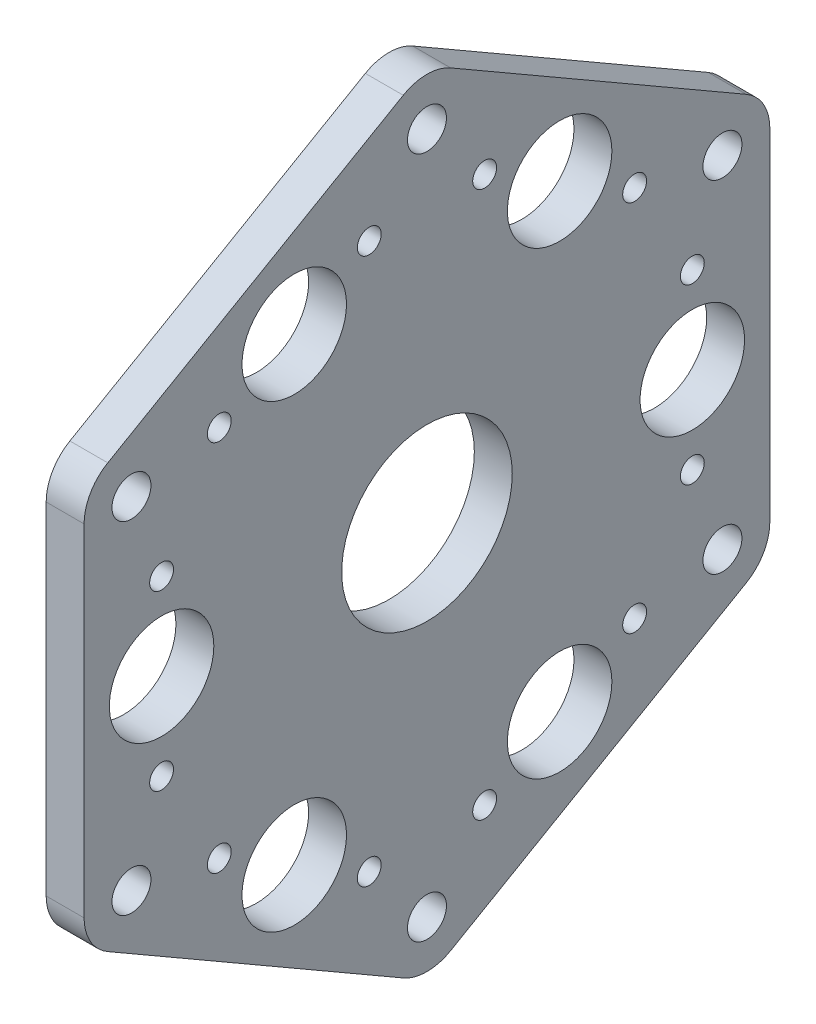
SolidWorks part; units mm, degrees
material "6061-T6 (SS)"
ref_plane "Front Plane" through (0, 0, 0) normal (0, 0, 1) x (1, 0, 0)
ref_plane "Top Plane" through (0, 0, 0) normal (0, 1, 0) x (1, 0, 0)
ref_plane "Right Plane" through (0, 0, 0) normal (1, 0, 0) x (0, 0, -1)
sketch "Sketch1" plane through (0, 0, 0) normal (1, 0, 0) x (0, 0, -1)
  line L0 (-57.4309, 28.575) -> (-57.4309, -28.575)
  line L1 (-53.4621, 35.4491) -> (-3.9687, 64.0241)
  line L2 (3.9688, 64.0241) -> (53.4621, 35.4491)
  line L3 (57.4309, 28.575) -> (57.4309, -28.575)
  line L4 (53.4621, -35.4491) -> (3.9687, -64.0241)
  line L5 (-53.4621, -35.4491) -> (-3.9688, -64.0241)
  circle A1 centre (0, -57.15) radius 3.2639 construction
  circle A3 centre (49.4934, -28.575) radius 3.2639 construction
  circle A5 centre (49.4934, 28.575) radius 3.2639 construction
  circle A8 centre (0, 57.15) radius 3.2639 construction
  circle A9 centre (-49.4934, 28.575) radius 3.2639 construction
  circle A10 centre (-49.4934, -28.575) radius 3.2639 construction
  circle A13 centre (0, -57.15) radius 3.2639
  circle A15 centre (49.4934, -28.575) radius 3.2639
  circle A17 centre (49.4934, 28.575) radius 3.2639
  circle A20 centre (0, 57.15) radius 3.2639
  circle A21 centre (-49.4934, 28.575) radius 3.2639
  circle A22 centre (-49.4934, -28.575) radius 3.2639
  circle A25 centre (-49.4934, -28.575) radius 7.9375
  circle A27 centre (-49.4934, 28.575) radius 7.9375
  circle A28 centre (0, 57.15) radius 7.9375
  circle A29 centre (49.4934, 28.575) radius 7.9375
  circle A30 centre (49.4934, -28.575) radius 7.9375
  circle A31 centre (0, -57.15) radius 7.9375
  dimension "D1" = 15.875
extrude "Boss-Extrude1" add sketch "Sketch1" along normal blind 6.35 contours A31 L4 A30 L3 A29 L2 A28 L1 A27 L0 A25 L5 | A27 A21 | A25 A22 | A28 A20 | A29 A17 | A30 A15 | A31 A13
sketch "Sketch2" plane through (0, 0, 0) normal (1, 0, 0) x (0, 0, -1)
  circle A0 centre (0, 0) radius 14.2875 construction
  circle A1 centre (-34.7853, -31.2431) radius 2 construction
  circle A2 centre (-22.225, -38.4948) radius 8.7503 construction
  circle A3 centre (-9.6647, -45.7465) radius 2 construction
  circle A4 centre (9.6647, -45.7465) radius 2 construction
  circle A5 centre (34.7853, -31.2431) radius 2 construction
  circle A6 centre (22.225, -38.4948) radius 8.7503 construction
  circle A7 centre (44.45, -14.5034) radius 2 construction
  circle A8 centre (44.45, 0) radius 8.7503 construction
  circle A9 centre (44.45, 14.5034) radius 2 construction
  circle A10 centre (34.7853, 31.2431) radius 2 construction
  circle A11 centre (9.6647, 45.7465) radius 2 construction
  circle A12 centre (-9.6647, 45.7465) radius 2 construction
  circle A13 centre (22.225, 38.4948) radius 8.7503 construction
  circle A14 centre (-34.7853, 31.2431) radius 2 construction
  circle A15 centre (-22.225, 38.4948) radius 8.7503 construction
  circle A16 centre (-44.45, -14.5034) radius 2 construction
  circle A17 centre (-44.45, 14.5034) radius 2 construction
  circle A18 centre (-44.45, 0) radius 8.7503 construction
  circle A19 centre (0, 0) radius 14.2875
  circle A20 centre (-34.7853, -31.2431) radius 2
  circle A21 centre (-22.225, -38.4948) radius 8.7503
  circle A22 centre (-9.6647, -45.7465) radius 2
  circle A23 centre (9.6647, -45.7465) radius 2
  circle A24 centre (34.7853, -31.2431) radius 2
  circle A25 centre (22.225, -38.4948) radius 8.7503
  circle A26 centre (44.45, -14.5034) radius 2
  circle A27 centre (44.45, 0) radius 8.7503
  circle A28 centre (44.45, 14.5034) radius 2
  circle A29 centre (34.7853, 31.2431) radius 2
  circle A30 centre (9.6647, 45.7465) radius 2
  circle A31 centre (-9.6647, 45.7465) radius 2
  circle A32 centre (22.225, 38.4948) radius 8.7503
  circle A33 centre (-34.7853, 31.2431) radius 2
  circle A34 centre (-22.225, 38.4948) radius 8.7503
  circle A35 centre (-44.45, -14.5034) radius 2
  circle A36 centre (-44.45, 14.5034) radius 2
  circle A37 centre (-44.45, 0) radius 8.7503
extrude "Cut-Extrude1" cut sketch "Sketch2" along normal through all
